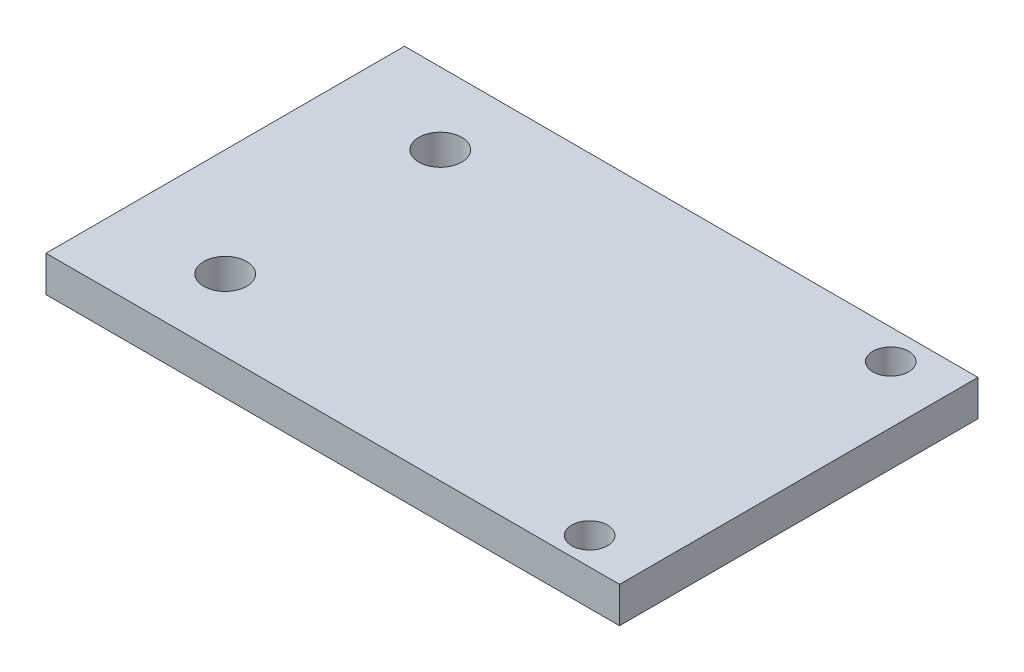
SolidWorks part; units mm, degrees
ref_plane "Front Plane" through (0, 0, 0) normal (0, 0, 1) x (1, 0, 0)
ref_plane "Top Plane" through (0, 0, 0) normal (0, 1, 0) x (1, 0, 0)
ref_plane "Right Plane" through (0, 0, 0) normal (1, 0, 0) x (0, 0, -1)
sketch "Sketch1" plane through (0, 0, 0) normal (0, 1, 0) x (1, 0, 0)
  line L1 (0, 0) -> (80, 0)
  line L2 (0, 0) -> (0, 50)
  line L3 (0, 50) -> (80, 50)
  line L4 (80, 0) -> (80, 50)
  circle A0 centre (15, 40) radius 3
  circle A1 centre (15, 10) radius 3
  dimension "D5" = 6
  dimension "D8" = 6
  dimension "D1" = 50
  dimension "D2" = 80
  dimension "D3" = 15
  dimension "D4" = 10
  dimension "D6" = 10
  dimension "D7" = 15
extrude "Boss-Extrude1" add sketch "Sketch1" along normal blind 5
sketch "Sketch2" plane through (0, 5, 0) normal (0, 1, 0) x (1, 0, 0)
  circle A0 centre (72, 3.828) radius 2.5
  circle A1 centre (72, 45.828) radius 2.5
extrude "Cut-Extrude1" cut sketch "Sketch2" against normal blind 10
